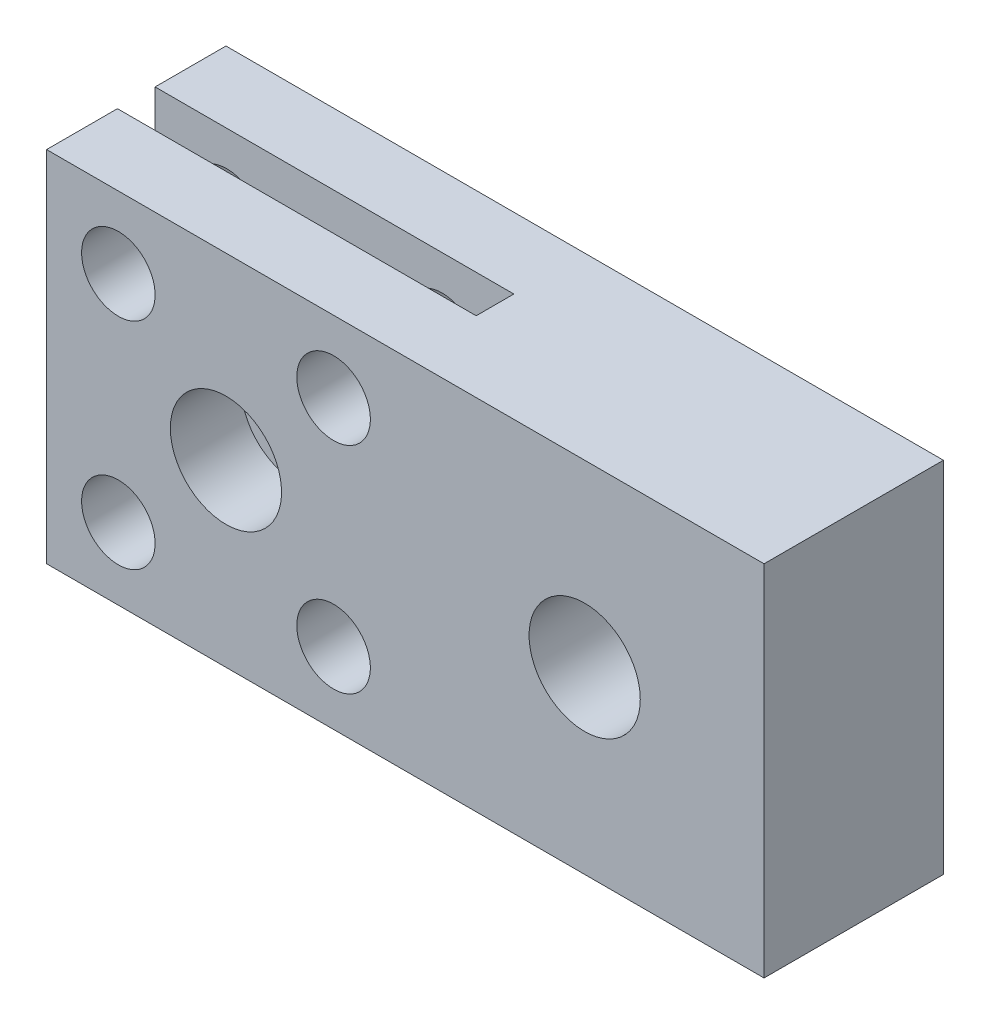
SolidWorks part; units mm, degrees
ref_plane "Plan de face" through (0, 0, 0) normal (0, 0, 1) x (1, 0, 0)
ref_plane "Plan de dessus" through (0, 0, 0) normal (0, 1, 0) x (1, 0, 0)
ref_plane "Plan de droite" through (0, 0, 0) normal (1, 0, 0) x (0, 0, -1)
sketch "Esquisse1" plane through (0, 0, 0) normal (0, 0, 1) x (1, 0, 0)
  line L1 (20, 10) -> (-20, 10)
  line L2 (20, 10) -> (20, -10)
  line L3 (20, -10) -> (-20, -10)
  line L4 (-20, 10) -> (-20, -10)
  line L5 (20, 10) -> (-20, -10) construction
  line L6 (20, -10) -> (-20, 10) construction
  point P0 (0, 0)
  dimension "D1" = 40
  dimension "D2" = 20
extrude "Boss.-Extru.1" add sketch "Esquisse1" along normal blind 10
sketch "Esquisse3" plane through (0, -10, 0) normal (0, -1, 0) x (-1, 0, 0)
  line L0 (20, -10) -> (20, 0) construction
  line L1 (40, -6.05) -> (0, -6.05)
  line L2 (40, -6.05) -> (40, -3.95)
  line L3 (40, -3.95) -> (0, -3.95)
  line L4 (0, -6.05) -> (0, -3.95)
  line L5 (40, -6.05) -> (0, -3.95) construction
  line L6 (40, -3.95) -> (0, -6.05) construction
  point P0 (20, -5)
  dimension "D1" = 2.1
  dimension "D2" = 20
extrude "Enlèv. mat.-Extru.2" cut sketch "Esquisse3" against normal through all
sketch "Esquisse4" plane through (0, 0, 0) normal (0, 0, -1) x (-1, 0, 0)
  line L0 (-20, 10) -> (20, 10) construction
  line L1 (20, 10) -> (20, -10) construction
  line L2 (0, 10) -> (0, -10) construction
  line L3 (20, -10) -> (-20, -10) construction
  circle A0 centre (16, 6) radius 2.05
  circle A1 centre (4, 6) radius 2.05
  circle A2 centre (4, -6) radius 2.05
  circle A3 centre (16, -6) radius 2.05
  dimension "D1" = 4.1
  dimension "D2" = 4
  dimension "D3" = 4
  dimension "D4" = 4
  dimension "D5" = 4
extrude "Enlèv. mat.-Extru.3" cut sketch "Esquisse4" against normal through all
sketch "Esquisse5" plane through (0, 0, 0) normal (0, 0, -1) x (-1, 0, 0)
  line L0 (-20, 10) -> (20, 10) construction
  line L1 (20, 10) -> (20, -10) construction
  line L2 (0, 13.7048) -> (0, -13.2251) construction
  circle A0 centre (10, 0) radius 3.1
  circle A1 centre (-10, 0) radius 3.1
  dimension "D1" = 6.2
  dimension "D2" = 10
  dimension "D3" = 10
extrude "Enlèv. mat.-Extru.4" cut sketch "Esquisse5" against normal blind 10
